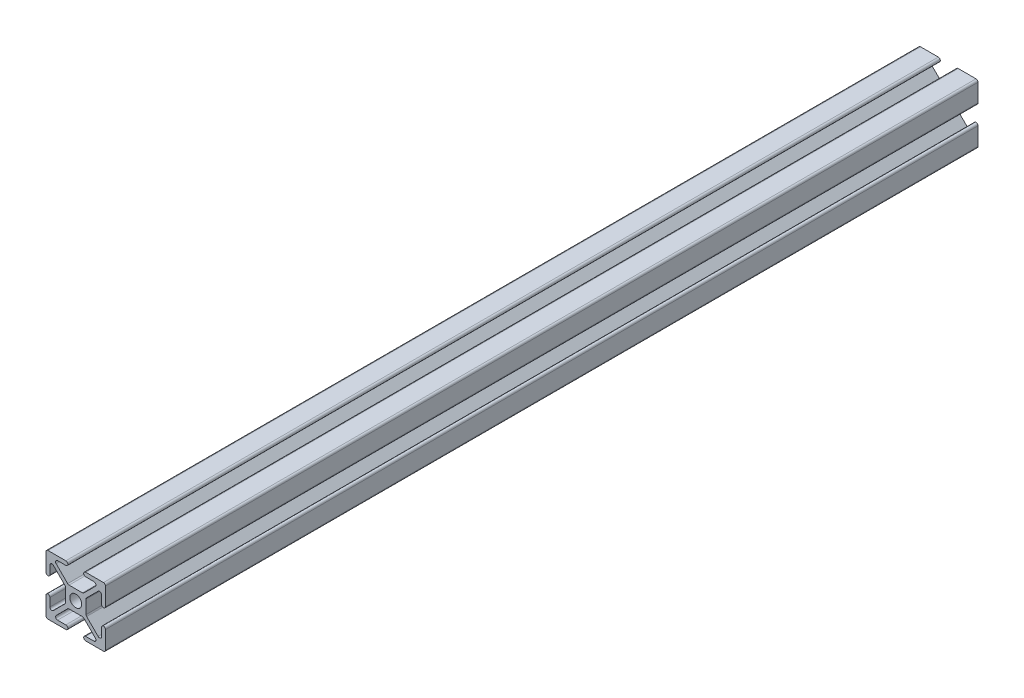
SolidWorks part; units mm, degrees
ref_plane "Alzado" through (0, 0, 0) normal (0, 0, 1) x (1, 0, 0)
ref_plane "Planta" through (0, 0, 0) normal (0, 1, 0) x (1, 0, 0)
ref_plane "Vista lateral" through (0, 0, 0) normal (1, 0, 0) x (0, 0, -1)
sketch "Croquis1" plane through (0, 0, 0) normal (0, 0, 1) x (1, 0, 0)
  line L1 (-14, 15) -> (14, 15)
  line L2 (-15, 14) -> (-15, -14)
  line L3 (-14, -15) -> (14, -15)
  line L4 (15, 14) -> (15, -14)
  line L5 (-15, 15) -> (15, -15) construction
  line L6 (-15, -15) -> (15, 15) construction
  arc A0 (-14, 15) -> (-15, 14) centre (-14, 14) ccw
  arc A1 (14, -15) -> (15, -14) centre (14, -14) ccw
  arc A2 (-14, -15) -> (-15, -14) centre (-14, -14) cw
  arc A3 (15, 14) -> (14, 15) centre (14, 14) ccw
  point P0 (0, 0)
  dimension "D3" = 1
  dimension "D4" = 1
  dimension "D1" = 30
  dimension "D2" = 30
extrude "Saliente-Extruir1" add sketch "Croquis1" against normal blind 440
sketch "Croquis2" plane through (0, 0, 0) normal (0, 0, 1) x (1, 0, 0)
  circle A0 centre (0, 0) radius 3
  dimension "D1" = 6
sketch "Croquis3" plane through (0, 0, 0) normal (0, 0, 1) x (1, 0, 0)
  line L0 (-15, 0) -> (15, 0) construction
  line L1 (4.0787, -5.4929) -> (9.8787, -11.2929)
  line L2 (-11.2929, 9.8787) -> (-5.4929, 4.0787)
  line L3 (-9.8787, 11.2929) -> (-4.0787, 5.4929)
  line L4 (-13, 9.1716) -> (-13, 5)
  line L5 (-15, 14) -> (-15, -14) construction
  line L6 (-5.2, 3.3716) -> (-5.2, -3.3716)
  line L7 (-9.1716, 13) -> (-5, 13)
  line L8 (9.8787, 11.2929) -> (4.0787, 5.4929)
  line L9 (11.2929, 9.8787) -> (5.4929, 4.0787)
  line L10 (-3.3716, 5.2) -> (3.3716, 5.2)
  line L11 (14, 15) -> (-14, 15) construction
  line L12 (13, 9.1716) -> (13, 5)
  line L13 (5.2, 3.3716) -> (5.2, -3.3716)
  line L14 (15, -14) -> (15, 14) construction
  line L15 (-9.1716, -13) -> (-5, -13)
  line L16 (-3.3716, -5.2) -> (3.3716, -5.2)
  line L17 (-14, -15) -> (14, -15) construction
  line L18 (-5.4929, -4.0787) -> (-11.2929, -9.8787)
  line L19 (5.4929, -4.0787) -> (11.2929, -9.8787)
  line L20 (-4.0787, -5.4929) -> (-9.8787, -11.2929)
  line L21 (5, -13) -> (9.1716, -13)
  line L22 (-13, -5) -> (-13, -9.1716)
  line L23 (13, -5) -> (13, -9.1716)
  line L24 (0, 15) -> (0, -5.2) construction
  line L34 (5, 13) -> (9.1716, 13)
  arc A0 (9.8787, 11.2929) -> (9.1716, 13) centre (9.1716, 12) ccw
  arc A1 (-9.8787, 11.2929) -> (-9.1716, 13) centre (-9.1716, 12) cw
  arc A2 (9.8787, 11.2929) -> (9.1716, 13) centre (9.1716, 12) ccw
  arc A3 (13, 9.1716) -> (11.2929, 9.8787) centre (12, 9.1716) ccw
  arc A4 (11.2929, -9.8787) -> (13, -9.1716) centre (12, -9.1716) ccw
  arc A5 (9.1716, -13) -> (9.8787, -11.2929) centre (9.1716, -12) ccw
  arc A6 (-9.1716, -13) -> (-9.8787, -11.2929) centre (-9.1716, -12) cw
  arc A7 (-11.2929, -9.8787) -> (-13, -9.1716) centre (-12, -9.1716) cw
  arc A8 (-13, 9.1716) -> (-11.2929, 9.8787) centre (-12, 9.1716) cw
  arc A9 (-4.0787, -5.4929) -> (-3.3716, -5.2) centre (-3.3716, -6.2) cw
  arc A10 (3.3716, -5.2) -> (4.0787, -5.4929) centre (3.3716, -6.2) cw
  arc A11 (5.4929, -4.0787) -> (5.2, -3.3716) centre (6.2, -3.3716) cw
  arc A12 (5.2, 3.3716) -> (5.4929, 4.0787) centre (6.2, 3.3716) cw
  arc A13 (3.3716, 5.2) -> (4.0787, 5.4929) centre (3.3716, 6.2) ccw
  arc A14 (-3.3716, 5.2) -> (-4.0787, 5.4929) centre (-3.3716, 6.2) cw
  arc A15 (-5.4929, -4.0787) -> (-5.2, -3.3716) centre (-6.2, -3.3716) ccw
  arc A16 (-5.2, 3.3716) -> (-5.4929, 4.0787) centre (-6.2, 3.3716) ccw
  circle A17 centre (-14, -5) radius 1
  circle A18 centre (-14, 5) radius 1
  circle A19 centre (-5, -14) radius 1
  circle A20 centre (5, -14) radius 1
  circle A21 centre (14, 5) radius 1
  circle A22 centre (14, -5) radius 1
  circle A23 centre (-5, 14) radius 1
  circle A24 centre (5, 14) radius 1
  point P20 (-11.5858, -13)
  point P30 (-13, -11.5858)
  point P43 (-3.7858, -5.2)
  point P50 (3.7858, -5.2)
  point P53 (5.2, -3.7858)
  point P62 (-5.2, -3.7858)
  line M2 (-15, 14) -> (-15, -14)
  line M4 (-14, -15) -> (14, -15)
  line M6 (15, -14) -> (15, 14)
  line M8 (14, 15) -> (-14, 15)
  dimension "D6" = 9.8
  dimension "D7" = 2
  dimension "D12" = 2
  dimension "D19" = 1
  dimension "D2" = 1
  dimension "D3" = 1
  dimension "D4" = 1
  dimension "D16" = 1
  dimension "D5" = 2
  dimension "D8" = 9.8
  dimension "D9" = 2
  dimension "D10" = 9.8
  dimension "D11" = 9.8
  dimension "D15" = 1
  dimension "D20" = 1
  dimension "D23" = 1
  dimension "D24" = 1
  dimension "D27" = 1
  dimension "D28" = 1
extrude "Cortar-Extruir1" cut sketch "Croquis2" against normal through all
extrude "Cortar-Extruir3" cut sketch "Croquis3" against normal through all contours A18 A17 L22 A7 L18 A15 L6 A16 L2 A8 L4 M2 | A24 A23 L7 A1 L3 A14 L10 A13 L8 A0 L34 M8 | A20 L21 A5 L1 A10 L16 A9 L20 A6 L15 A19 M4 | A22 A21 L12 A3 L9 A12 L13 A11 L19 A4 L23 M6
